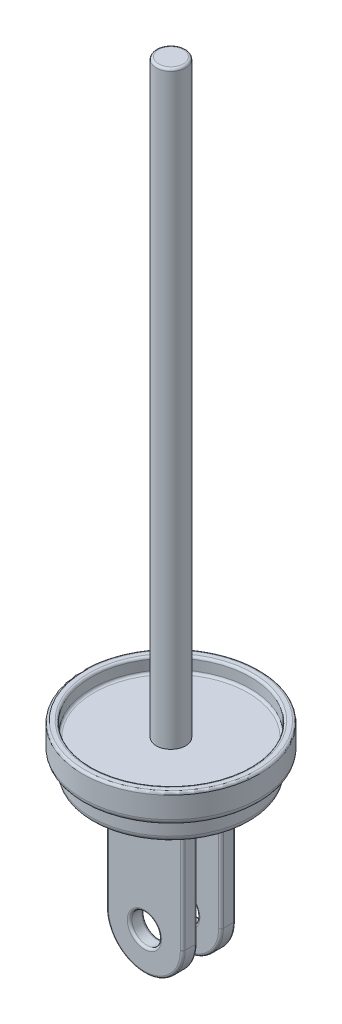
SolidWorks part; units mm, degrees
ref_plane "Front Plane" through (0, 0, 0) normal (0, 0, 1) x (1, 0, 0)
ref_plane "Top Plane" through (0, 0, 0) normal (0, 1, 0) x (1, 0, 0)
ref_plane "Right Plane" through (0, 0, 0) normal (1, 0, 0) x (0, 0, -1)
sketch "Sketch1" plane through (0, 0, 0) normal (0, 1, 0) x (1, 0, 0)
  circle A0 centre (0, 0) radius 6.75
  circle A1 centre (0, 0) radius 1.25 construction
  dimension "D1" = 13.5
  dimension "D2" = 2.5
extrude "Boss-Extrude1" add sketch "Sketch1" along normal blind 3
sketch "Sketch2" plane through (0, 3, 0) normal (0, 1, 0) x (1, 0, 0)
  circle A0 centre (0, 0) radius 1.25 construction
  circle A1 centre (0, 0) radius 1.25
extrude "Boss-Extrude2" add sketch "Sketch2" along normal blind 50
sketch "Sketch3" plane through (0, 0, 0) normal (0, 0, 1) x (1, 0, 0)
  line L0 (6.75, 0) -> (-6.75, 0) construction
  line L1 (3.25, -10) -> (3.25, 0)
  line L2 (3.25, 0) -> (-3.25, 0)
  line L3 (-3.25, 0) -> (-3.25, -10)
  circle A0 centre (0, -10) radius 1.25
  arc A1 (-3.25, -10) -> (3.25, -10) centre (0, -10) ccw
  circle A2 centre (0, -10) radius 3.25 construction
  dimension "D2" = 2.5
  dimension "D1" = 10
  dimension "D3" = 2
extrude "Boss-Extrude3" add sketch "Sketch3" along normal blind 1.25 from offset 1
mirror "Mirror1" about plane through (0, 0, 0) normal (0, 0, 1) of "Boss-Extrude3"
sketch "Sketch4" plane through (0, 3, 0) normal (0, 1, 0) x (1, 0, 0)
  circle A0 centre (0, 0) radius 7.5
  circle A1 centre (0, 0) radius 6.75
  circle A2 centre (0, 0) radius 6.75
  dimension "D1" = 0
  dimension "D2" = 0.75
extrude "Boss-Extrude4" add sketch "Sketch4" along normal blind 1.25 and the other way blind 1.25
fillet "Fillet1" radius 0.5 2 edges at (0, 1.75, 7.5) (0, 0, 6.75)
fillet "Fillet2" radius 0.2 24 edges at (1.25, -10, 1) (1.25, -10, 2.25) (3.25, -5, 1) (0, 0, 1) (-3.25, -5, 1) (0, -13.25, 2.25) (3.25, -5, 2.25) (0, 0, 2.25) (-3.25, -5, 2.25) (-3.25, 0, 1.625) (3.25, 0, 1.625) (0, -13.25, 1) (1.25, -10, -1) (1.25, -10, -2.25) (0, -13.25, -1) (-3.25, -5, -1) (0, 0, -1) (3.25, -5, -1) (-3.25, -5, -2.25) (0, 0, -2.25) (3.25, -5, -2.25) (3.25, 0, -1.625) (-3.25, 0, -1.625) (0, -13.25, -2.25)
fillet "Fillet3" radius 0.2 3 edges at (0, 4.25, 6.75) (0, 4.25, 7.5) (0, 3, 6.75)
fillet "Fillet4" radius 0.2 1 edges at (0, 53, 1.25)
sketch "Sketch5" plane through (0, 3, 0) normal (0, 1, 0) x (1, 0, 0)
  circle A0 centre (0, 0) radius 6
  dimension "D1" = 12
